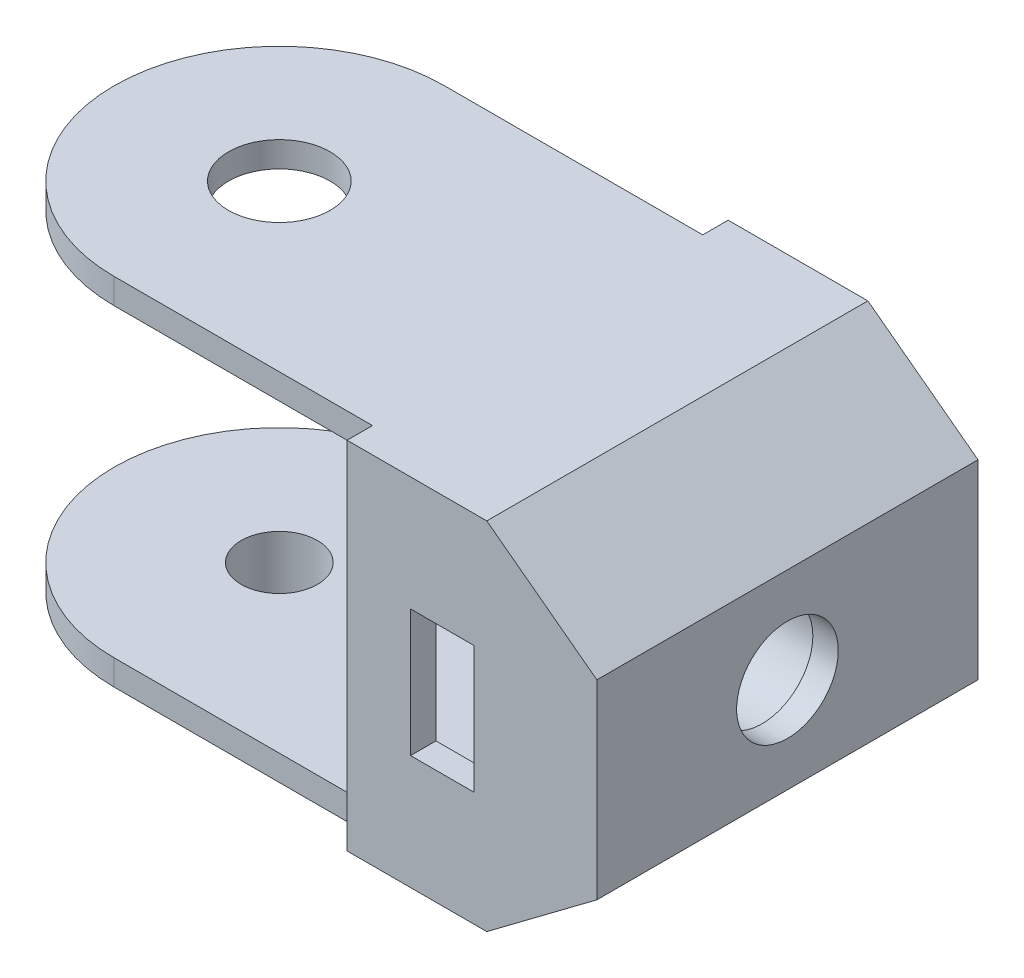
SolidWorks part; units mm, degrees
ref_plane "Front Plane" through (0, 0, 0) normal (0, 0, 1) x (1, 0, 0)
ref_plane "Top Plane" through (0, 0, 0) normal (0, 1, 0) x (1, 0, 0)
ref_plane "Right Plane" through (0, 0, 0) normal (1, 0, 0) x (0, 0, -1)
sketch "Sketch1" plane through (0, 0, 0) normal (0, 1, 0) x (1, 0, 0)
  line L1 (40, 13) -> (0, 13)
  line L2 (40, 13) -> (40, -13)
  line L3 (40, -13) -> (0, -13)
  arc A0 (0, 13) -> (0, -13) centre (0, 0) ccw
  dimension "D1" = 26
  dimension "D2" = 40
extrude "Boss-Extrude1" add sketch "Sketch1" along normal blind 2
sketch "Sketch2" plane through (0, 2, 0) normal (0, 1, 0) x (1, 0, 0)
  line L0 (0, -13) -> (40, -13) construction
  line L1 (40, 13) -> (38, 13)
  line L2 (40, 13) -> (40, -13)
  line L3 (40, -13) -> (38, -13)
  line L4 (38, 13) -> (38, -13)
  dimension "D1" = 2
extrude "Boss-Extrude2" add sketch "Sketch2" along normal blind 24
sketch "Sketch3" plane through (0, 26, 0) normal (0, 1, 0) x (1, 0, 0)
  line L1 (40, -13) -> (0, -13)
  line L2 (40, -13) -> (40, 13)
  line L3 (40, 13) -> (0, 13)
  arc A0 (0, 13) -> (0, -13) centre (0, 0) ccw
extrude "Boss-Extrude3" add sketch "Sketch3" along normal blind 2
sketch "Sketch4" plane through (40, 0, 0) normal (1, 0, 0) x (0, 0, -1)
  line L0 (-13, 28) -> (13, 28) construction
  line L1 (-13, 28) -> (-13, 0) construction
  circle A0 centre (0, 14) radius 4
  point P5 (0, 28)
  point P8 (-13, 14)
  dimension "D1" = 8
extrude "Cut-Extrude1" cut sketch "Sketch4" against normal blind 2
sketch "Sketch5" plane through (0, 0, 13) normal (0, 0, 1) x (1, 0, 0)
  line L0 (38, 5) -> (34, 2)
  line L9 (34, 2) -> (31.3333, 0)
  line L10 (0, 0) -> (40, 0) construction
  line L11 (31.3333, 0) -> (31.3333, 2)
  line L12 (0, 2) -> (38, 2) construction
  line L13 (31.3333, 2) -> (40, 8.5)
  line L14 (40, 28) -> (40, 0) construction
  line L15 (40, 8.5) -> (40, 6.5)
  line L16 (40, 6.5) -> (38, 5)
  line L17 (40, 14) -> (19.1052, 14) construction
  line L18 (40, 21.5) -> (38, 23)
  line L19 (40, 19.5) -> (40, 21.5)
  line L20 (31.3333, 26) -> (40, 19.5)
  line L21 (31.3333, 28) -> (31.3333, 26)
  line L22 (34, 26) -> (31.3333, 28)
  line L23 (38, 23) -> (34, 26)
  dimension "D5" = 2
extrude "Boss-Extrude4" add sketch "Sketch5" against normal up to surface (26 mm away) up to face at (19.5, 14, -13)
sketch "Sketch6" plane through (0, 0, 13) normal (0, 0, 1) x (1, 0, 0)
  line L0 (38, 5) -> (31.3333, 0)
  line L1 (0, 0) -> (40, 0) construction
  line L2 (31.3333, 0) -> (40, 0)
  line L3 (40, 0) -> (40, 6.5)
  line L4 (40, 28) -> (40, 0) construction
  line L5 (40, 6.5) -> (38, 5)
  line L6 (34, 2) -> (38, 5) construction
  line L7 (40, 14) -> (25.7632, 14) construction
  line L8 (40, 28) -> (40, 21.5)
  line L9 (31.3333, 28) -> (40, 28)
  line L10 (38, 23) -> (31.3333, 28)
  line L11 (40, 21.5) -> (38, 23)
extrude "Cut-Extrude2" cut sketch "Sketch6" against normal up to surface (26 mm away) up to face at (36.6667, 3, -13)
sketch "Sketch7" plane through (0, 0, 13) normal (0, 0, 1) x (1, 0, 0)
  line L0 (40, 21.5) -> (31.3333, 28)
  line L1 (31.3333, 28) -> (20.3333, 28)
  line L2 (0, 28) -> (31.3333, 28) construction
  line L3 (20.3333, 28) -> (20.3333, 0)
  line L4 (0, 0) -> (31.3333, 0) construction
  line L5 (20.3333, 0) -> (31.3333, 0)
  line L6 (31.3333, 0) -> (40, 6.5)
  line L7 (40, 6.5) -> (40, 21.5)
  dimension "D1" = 11
extrude "Boss-Extrude5" add sketch "Sketch7" along normal blind 2
ref_plane "Plane1" through (0, 0, 0) normal (0, 0, 1) x (1, 0, 0)
mirror "Mirror1" about plane through (0, 0, 0) normal (0, 0, 1) of "Boss-Extrude5"
sketch "Sketch8" plane through (38, 0, 0) normal (-1, 0, 0) x (0, 0, 1)
  circle A0 centre (0, 14) radius 4.4884
  circle A1 centre (0, 14) radius 7.515
extrude "Boss-Extrude6" add sketch "Sketch8" along normal blind 4
sketch "Sketch9" plane through (0, 0, 0) normal (0, -1, 0) x (1, 0, 0)
  circle A0 centre (0, 0) radius 3
  dimension "D1" = 6
extrude "Cut-Extrude3" cut sketch "Sketch9" against normal blind 10
sketch "Sketch10" plane through (0, 28, 0) normal (0, 1, 0) x (1, 0, 0)
  circle A0 centre (0, 0) radius 4
  dimension "D1" = 8
extrude "Cut-Extrude4" cut sketch "Sketch10" against normal blind 10
sketch "Sketch11" plane through (0, 0, 0) normal (0, -1, 0) x (1, 0, 0)
  circle A0 centre (0, 0) radius 3
  circle A1 centre (0, 0) radius 4
  dimension "D1" = 8
  dimension "D2" = 6
extrude "Boss-Extrude7" add sketch "Sketch11" along normal blind 7
sketch "Sketch12" plane through (0, -7, 0) normal (0, -1, 0) x (1, 0, 0)
  circle A0 centre (0, 0) radius 4
extrude "Boss-Extrude8" add sketch "Sketch12" along normal blind 1
sketch "Sketch13" plane through (0, 0, 15) normal (0, 0, 1) x (1, 0, 0)
  line L0 (20.3333, 28) -> (20.3333, 0) construction
  line L1 (25.3333, 19) -> (30.3333, 19)
  line L2 (25.3333, 19) -> (25.3333, 9)
  line L3 (25.3333, 9) -> (30.3333, 9)
  line L4 (30.3333, 19) -> (30.3333, 9)
  line L5 (40, 6.5) -> (40, 21.5) construction
  point P8 (40, 14)
  point P9 (30.3333, 14)
  dimension "D1" = 10
  dimension "D2" = 5
  dimension "D3" = 5
extrude "Cut-Extrude5" cut sketch "Sketch13" against normal blind 10
sketch "Sketch14" plane through (0, 0, -15) normal (0, 0, -1) x (-1, 0, 0)
  line L1 (-30.3333, 19) -> (-25.3333, 19)
  line L2 (-30.3333, 19) -> (-30.3333, 9)
  line L3 (-30.3333, 9) -> (-25.3333, 9)
  line L4 (-25.3333, 19) -> (-25.3333, 9)
extrude "Cut-Extrude6" cut sketch "Sketch14" against normal blind 4
